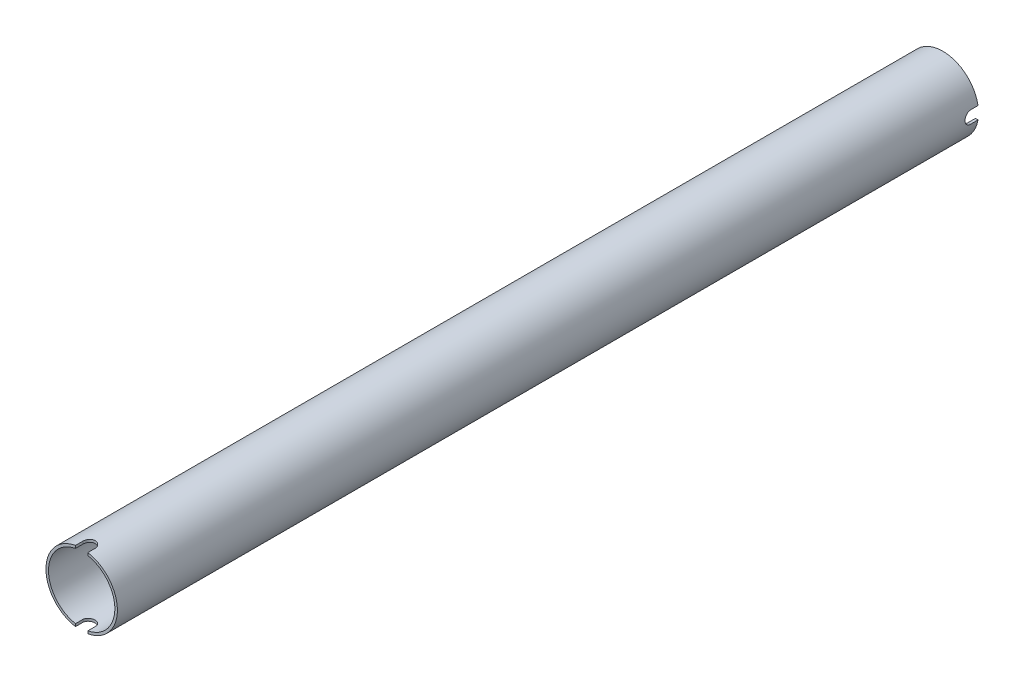
SolidWorks part; units mm, degrees
ref_plane "Front Plane" through (0, 0, 0) normal (0, 0, 1) x (1, 0, 0)
ref_plane "Top Plane" through (0, 0, 0) normal (0, 1, 0) x (1, 0, 0)
ref_plane "Right Plane" through (0, 0, 0) normal (1, 0, 0) x (0, 0, -1)
sketch "Sketch1" plane through (0, 0, 0) normal (1, 0, 0) x (0, 0, -1)
  line L0 (-150.0188, 11.557) -> (150.0188, 11.557)
  line L1 (150.0188, 11.557) -> (150.0188, 12.446)
  line L2 (150.0188, 12.446) -> (-150.0188, 12.446)
  line L3 (-150.0188, 12.446) -> (-150.0188, 11.557)
  line L4 (-90.6759, 0) -> (171.3224, 0) construction
  dimension "D1" = 12.446
  dimension "D2" = 0.889
  dimension "D3" = 300.0375
  dimension "D4" = 150.0188
revolve "Revolve1" add sketch "Sketch1" angle 360 about L4
sketch "Sketch2" plane through (0, 0, 0) normal (0, 1, 0) x (1, 0, 0)
  line L0 (0, -155.0987) -> (0, -147.4788) construction
  line L1 (-2.159, -155.0987) -> (-2.159, -147.4788)
  line L2 (2.159, -155.0987) -> (2.159, -147.4788)
  line L3 (-12.446, -150.0188) -> (12.446, -150.0188) construction
  arc A0 (-2.159, -155.0987) -> (2.159, -155.0987) centre (0, -155.0987) ccw
  arc A1 (2.159, -147.4788) -> (-2.159, -147.4788) centre (0, -147.4788) ccw
  point P3 (0, -151.2888)
  dimension "D1" = 2.54
  dimension "D2" = 7.62
extrude "Cut-Extrude1" cut sketch "Sketch2" against normal mid plane 25.4
sketch "Sketch3" plane through (0, 0, 0) normal (1, 0, 0) x (0, 0, -1)
  line L0 (155.0987, 0) -> (147.4788, 0) construction
  line L1 (155.0987, -2.159) -> (147.4788, -2.159)
  line L2 (155.0987, 2.159) -> (147.4788, 2.159)
  line L3 (150.0188, -12.446) -> (150.0188, 12.446) construction
  arc A0 (155.0987, -2.159) -> (155.0987, 2.159) centre (155.0987, 0) ccw
  arc A1 (147.4788, 2.159) -> (147.4788, -2.159) centre (147.4788, 0) ccw
  point P3 (151.2888, 0)
  dimension "D1" = 2.54
extrude "Cut-Extrude2" cut sketch "Sketch3" against normal mid plane 25.4
scale "Scale1" scale about centroid uniform scaling yes scale factor 0.6
